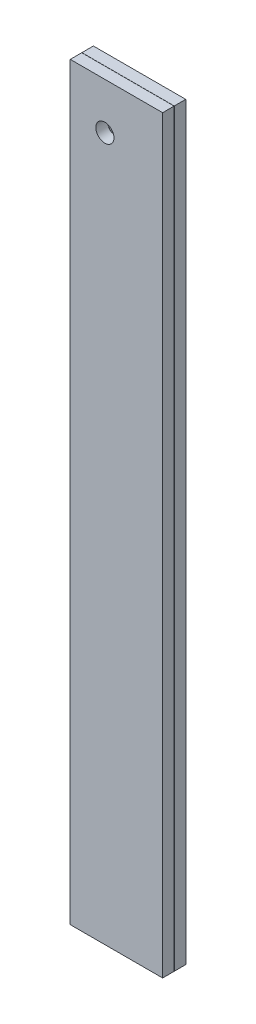
SolidWorks part; units mm, degrees
ref_plane "Alzado" through (0, 0, 0) normal (0, 0, 1) x (1, 0, 0)
ref_plane "Planta" through (0, 0, 0) normal (0, 1, 0) x (1, 0, 0)
ref_plane "Vista lateral" through (0, 0, 0) normal (1, 0, 0) x (0, 0, -1)
sketch "Croquis2" plane through (0, 0, 0) normal (0, 0, 1) x (1, 0, 0)
  line L0 (0, 0) -> (50.8, 0)
  line L1 (50.8, 0) -> (50.8, -361.2957)
  line L2 (50.8, -361.2957) -> (50.8, -412.0957)
  line L3 (50.8, -412.0957) -> (0, -412.0957)
  line L4 (0, -412.0957) -> (0, 0)
  dimension "D1" = 50.8
  dimension "D2" = 412.0957
extrude "Saliente-Extruir1" add sketch "Croquis2" along normal blind 6.31
sketch "Croquis3" plane through (50.8, 0, 0) normal (1, 0, 0) x (0, 0, -1)
  line L0 (-6.31, 0) -> (-6.41, 0)
  line L1 (-6.41, 0) -> (-12.72, 0)
  line L2 (-12.72, 0) -> (-12.72, -412.0957)
  line L3 (-12.72, -412.0957) -> (-6.41, -412.0957)
  line L4 (-6.41, 0) -> (-6.41, -412.0957)
  dimension "D1" = 0.1
  dimension "D2" = 6.31
extrude "Saliente-Extruir2" add sketch "Croquis3" against normal blind 50.8 separate body contours L4 L1 L2 L3
sketch "Croquis4" plane through (0, 0, 12.72) normal (0, 0, 1) x (1, 0, 0)
  line L0 (19.04, -25.4) -> (22.1587, -25.4) construction
  circle A0 centre (19.04, -25.4) radius 5
  dimension "D1" = 10
extrude "Cortar-Extruir1" cut sketch "Croquis4" against normal blind 31
sketch "Croquis5" plane through (0, 0, 12.72) normal (0, 0, 1) x (1, 0, 0)
  line L0 (13.0802, -424.1767) -> (12.7, -429.1622) construction
  line L1 (12.7, -429.1622) -> (38.1, -454.5622) construction
  circle A0 centre (12.7, -429.1622) radius 5 construction
  circle A1 centre (12.7, -429.1622) radius 5
  circle A2 centre (38.1, -454.5622) radius 5
  dimension "D1" = 10
  dimension "D2" = 10
